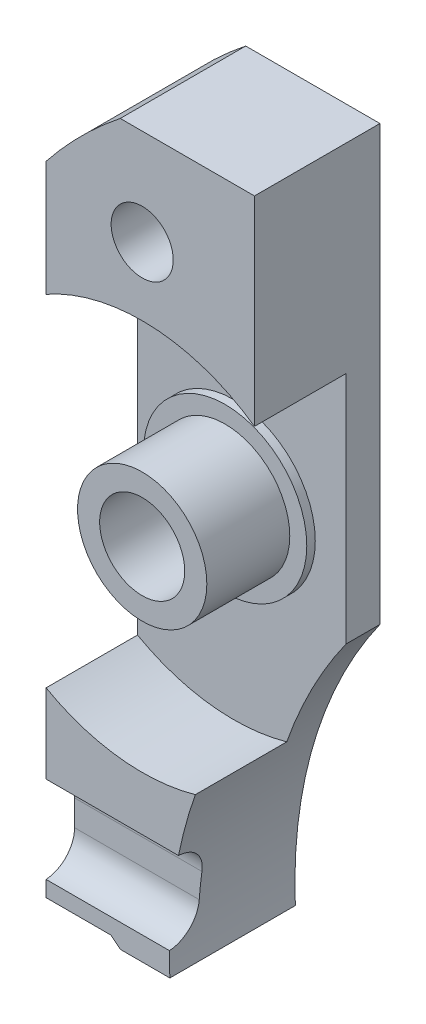
SolidWorks part; units mm, degrees
material "ABS"
ref_plane "Front Plane" through (0, 0, 0) normal (0, 0, 1) x (1, 0, 0)
ref_plane "Top Plane" through (0, 0, 0) normal (0, 1, 0) x (1, 0, 0)
ref_plane "Right Plane" through (0, 0, 0) normal (1, 0, 0) x (0, 0, -1)
sketch "Sketch1" plane through (0, 0, 0) normal (0, 0, 1) x (1, 0, 0)
  line L1 (-6.125, -21.15) -> (6.125, -21.15)
  line L2 (-6.125, -21.15) -> (-6.125, 21.15)
  line L3 (-6.125, 21.15) -> (6.125, 21.15)
  line L4 (6.125, -21.15) -> (6.125, 21.15)
  line L5 (-6.125, -21.15) -> (6.125, 21.15) construction
  line L6 (-6.125, 21.15) -> (6.125, -21.15) construction
  point P0 (0, 0)
  dimension "D1" = 12.25
  dimension "D2" = 42.3
extrude "Boss-Extrude1" add sketch "Sketch1" along normal blind 7.375
sketch "Sketch2" plane through (0, 0, 7.375) normal (0, 0, 1) x (1, 0, 0)
  line L0 (6.125, 21.15) -> (-6.125, 21.15) construction
  line L1 (-6.125, 21.15) -> (-6.125, -21.15) construction
  circle A0 centre (-0.475, 15.5) radius 1.825
  circle A1 centre (-0.475, 0) radius 2.5
  dimension "D1" = 3.65
  dimension "D2" = 5
  dimension "D3" = 5.65
  dimension "D4" = 5.65
  dimension "D5" = 15.5
extrude "Cut-Extrude1" cut sketch "Sketch2" against normal through all
sketch "Sketch3" plane through (0, 0, 7.375) normal (0, 0, 1) x (1, 0, 0)
  line L13 (-6.125, -21.15) -> (-6.125, -16.784)
  line L14 (-6.125, -21.15) -> (-1.7575, -21.15)
  line L15 (-6.125, 16.7898) -> (-6.125, 21.15)
  line L16 (-6.125, 21.15) -> (-1.7648, 21.15)
  line L17 (6.125, -4.3518) -> (6.125, -21.15)
  line L18 (6.125, -21.15) -> (1.1519, -21.15)
  arc A3 (-1.7575, -21.15) -> (-6.125, -16.784) centre (15.0221, 0.0029) cw
  arc A4 (1.1519, -21.15) -> (6.125, -4.3518) centre (28.1274, -20.0009) cw
  arc A5 (-6.125, 16.7898) -> (-1.7648, 21.15) centre (15.0221, 0.0029) cw
  dimension "D1" = 27
  dimension "D2" = 27
  dimension "D3" = 16.7982
  dimension "D4" = 4.9731
  dimension "D5" = 4.3675
  dimension "D6" = 27
  dimension "D7" = 4.366
  dimension "D8" = 4.3602
  dimension "D9" = 4.3602
extrude "Cut-Extrude2" cut sketch "Sketch3" against normal through all
sketch "Sketch4" plane through (0, 0, 7.375) normal (0, 0, 1) x (1, 0, 0)
  circle A0 centre (-0.475, 0) radius 11.5
  dimension "D1" = 23
extrude "Cut-Extrude3" cut sketch "Sketch4" against normal blind 5.375
sketch "Sketch5" plane through (0, 0, 2) normal (0, 0, 1) x (1, 0, 0)
  circle A0 centre (-0.475, 0) radius 4.8
  circle A1 centre (-0.475, 0) radius 2.5 construction
  circle A2 centre (-0.475, 0) radius 2.5
  dimension "D1" = 9.6
extrude "Boss-Extrude2" add sketch "Sketch5" along normal blind 0.5
sketch "Sketch6" plane through (0, 0, 2.5) normal (0, 0, 1) x (1, 0, 0)
  circle A0 centre (-0.475, 0) radius 3.8
  circle A1 centre (-0.475, 0) radius 2.5 construction
  circle A2 centre (-0.475, 0) radius 2.5
  dimension "D1" = 7.6
extrude "Boss-Extrude3" add sketch "Sketch6" along normal blind 4.875
sketch "Sketch7" plane through (-6.125, 0, 0) normal (1, 0, 0) x (0, 0, -1)
  line L0 (0, -4.3518) -> (0, 21.15) construction
  line L2 (-7.375, -13.7212) -> (-7.375, -20.6988)
  line L5 (-7.375, 21.15) -> (-7.375, 9.4175) construction
  line L6 (-7.375, -10.0164) -> (-2, -10.0164) construction
  arc A0 (-7.375, -20.6988) -> (-7.375, -13.7212) centre (-6, -17.21) ccw
  dimension "D1" = 7.5
  dimension "D2" = 6
  dimension "D3" = 7.1936
extrude "Boss-Extrude4" add sketch "Sketch7" along normal up to next
sketch "Sketch8" plane through (-6.125, 0, 0) normal (1, 0, 0) x (0, 0, -1)
  line L0 (-7.5, -17.9736) -> (-7.5, -16.4595) construction
  line L1 (-9.3, -17.9736) -> (-9.3, -16.4595)
  line L2 (-5.7, -17.9736) -> (-5.7, -16.4595)
  line L3 (0, -4.3518) -> (0, 21.15) construction
  line L5 (-7.375, -10.0164) -> (-2, -10.0164) construction
  arc A0 (-9.3, -17.9736) -> (-5.7, -17.9736) centre (-7.5, -17.9736) ccw
  arc A1 (-5.7, -16.4595) -> (-9.3, -16.4595) centre (-7.5, -16.4595) ccw
  point P2 (-7.5, -17.2165)
  dimension "D4" = 6.4431
  dimension "D1" = 3.6
  dimension "D2" = 7.5
  dimension "D3" = 1.5141
extrude "Cut-Extrude4" cut sketch "Sketch8" along normal through all
